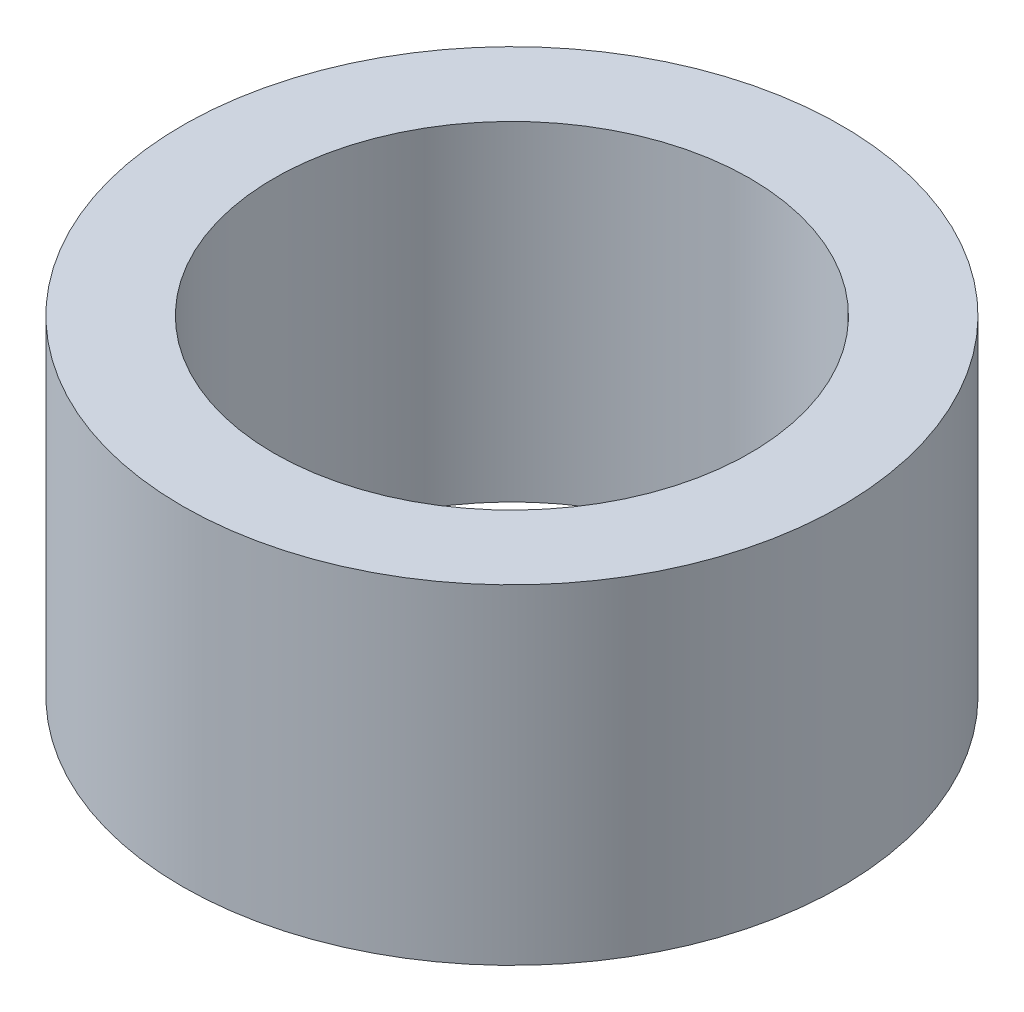
SolidWorks part; units mm, degrees
material "ABS"
ref_plane "Front Plane" through (0, 0, 0) normal (0, 0, 1) x (1, 0, 0)
ref_plane "Top Plane" through (0, 0, 0) normal (0, 1, 0) x (1, 0, 0)
ref_plane "Right Plane" through (0, 0, 0) normal (1, 0, 0) x (0, 0, -1)
sketch "Sketch1" plane through (0, 0, 0) normal (0, 1, 0) x (1, 0, 0)
  circle A0 centre (0, 0) radius 3.302
  circle A1 centre (0, 0) radius 4.572
  dimension "D1" = 6.604
  dimension "D2" = 9.144
extrude "Boss-Extrude1" add sketch "Sketch1" along normal blind 4.572
